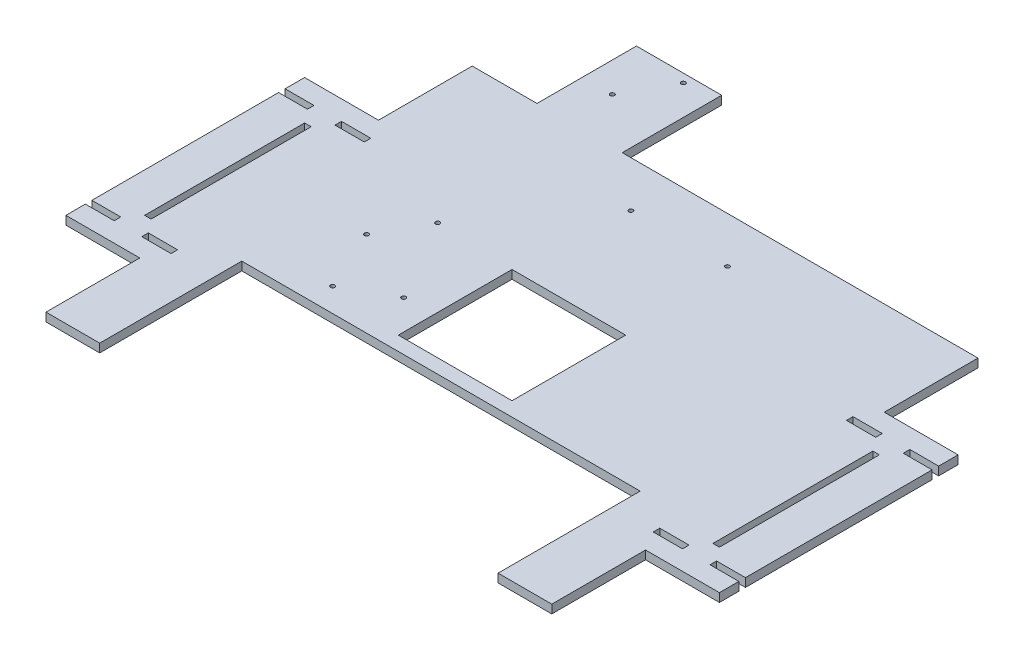
SolidWorks part; units mm, degrees
ref_plane "Front Plane" through (0, 0, 0) normal (0, 0, 1) x (1, 0, 0)
ref_plane "Top Plane" through (0, 0, 0) normal (0, 1, 0) x (1, 0, 0)
ref_plane "Right Plane" through (0, 0, 0) normal (1, 0, 0) x (0, 0, -1)
sketch "Sketch1" plane through (0, 0, 0) normal (0, 1, 0) x (1, 0, 0)
  line L1 (-57.5, -75) -> (57.5, -75)
  line L2 (-57.5, -75) -> (-57.5, 75)
  line L3 (-57.5, 75) -> (57.5, 75)
  line L4 (57.5, -75) -> (57.5, 75)
  line L5 (-57.5, -75) -> (57.5, 75) construction
  line L6 (-57.5, 75) -> (57.5, -75) construction
  point P0 (0, 0)
  dimension "D1" = 115
  dimension "D2" = 150
extrude "Boss-Extrude1" add sketch "Sketch1" against normal blind 3
sketch "Sketch2" plane through (0, 0, 0) normal (0, 1, 0) x (1, 0, 0)
  line L0 (0, 0) -> (-57.5, 75) construction
  line L1 (-57.5, 75) -> (-57.5, -75) construction
  line L2 (57.5, 75) -> (-57.5, 75) construction
  line L3 (0, 0) -> (57.5, 75) construction
  line L4 (57.5, -75) -> (57.5, 75) construction
  line L5 (0, 0) -> (-57.5, -75) construction
  line L6 (0, 0) -> (57.5, -75) construction
  line L15 (31.5, -42) -> (57.5, -42)
  line L16 (57.5, -42) -> (57.5, -108)
  line L17 (57.5, -108) -> (31.5, -108)
  line L18 (31.5, -108) -> (31.5, -42)
  line L19 (31.5, 108) -> (57.5, 108)
  line L20 (57.5, 108) -> (57.5, 42)
  line L21 (57.5, 42) -> (31.5, 42)
  line L22 (31.5, 42) -> (31.5, 108)
  line L23 (-57.5, -75) -> (57.5, -75) construction
  line L24 (12.6, -86.8) -> (12.6, -53.3) construction
  line L25 (-57.5, -75) -> (12.6, -75)
  line L26 (-57.5, -75) -> (-57.5, -25)
  line L27 (-57.5, -25) -> (12.6, -25)
  line L28 (12.6, -75) -> (12.6, -25)
  dimension "D7" = 66
  dimension "D8" = 26
  dimension "D9" = 66
  dimension "D10" = 26
  dimension "D11" = 33
  dimension "D12" = 33
  dimension "D2" = 50
extrude "Cut-Extrude1" cut sketch "Sketch2" against normal blind 3
sketch "Sketch5" plane through (0, -3, 0) normal (0, -1, 0) x (1, 0, 0)
  line L0 (57.5, -33) -> (57.5, -35) construction
  line L1 (57.5, -35) -> (47.5, -35) construction
  line L2 (47.5, -33) -> (57.5, -33) construction
  line L3 (47.5, -35) -> (47.5, -33) construction
  line L4 (37.5, -33) -> (37.5, -35) construction
  line L5 (37.5, -35) -> (27.5, -35) construction
  line L6 (27.5, -35) -> (27.5, -33) construction
  line L7 (27.5, -33) -> (37.5, -33) construction
  line L8 (43.5, -28) -> (41.5, -28) construction
  line L9 (41.5, -28) -> (41.5, 28) construction
  line L10 (43.5, 28) -> (43.5, -28) construction
  line L11 (41.5, 28) -> (43.5, 28) construction
  line L12 (57.5, 35) -> (57.5, 33) construction
  line L13 (57.5, 33) -> (47.5, 33) construction
  line L14 (47.5, 35) -> (57.5, 35) construction
  line L15 (47.5, 33) -> (47.5, 35) construction
  line L16 (27.5, 33) -> (27.5, 35) construction
  line L17 (37.5, 33) -> (27.5, 33) construction
  line L18 (37.5, 35) -> (37.5, 33) construction
  line L19 (27.5, 35) -> (37.5, 35) construction
  line L20 (57.5, -33) -> (57.5, -35) construction
  line L21 (57.5, -35) -> (47.5, -35) construction
  line L22 (47.5, -33) -> (57.5, -33) construction
  line L23 (47.5, -35) -> (47.5, -33) construction
  line L24 (37.5, -33) -> (37.5, -35) construction
  line L25 (37.5, -35) -> (27.5, -35) construction
  line L26 (27.5, -35) -> (27.5, -33) construction
  line L27 (27.5, -33) -> (37.5, -33) construction
  line L28 (43.5, -28) -> (41.5, -28) construction
  line L29 (41.5, -28) -> (41.5, 28) construction
  line L30 (43.5, 28) -> (43.5, -28) construction
  line L31 (41.5, 28) -> (43.5, 28) construction
  line L32 (57.5, 35) -> (57.5, 33) construction
  line L33 (57.5, 33) -> (47.5, 33) construction
  line L34 (47.5, 35) -> (57.5, 35) construction
  line L35 (47.5, 33) -> (47.5, 35) construction
  line L36 (27.5, 33) -> (27.5, 35) construction
  line L37 (37.5, 33) -> (27.5, 33) construction
  line L38 (37.5, 35) -> (37.5, 33) construction
  line L39 (27.5, 35) -> (37.5, 35) construction
  line L40 (27.35, 35.15) -> (37.65, 35.15)
  line L41 (37.65, 35.15) -> (37.65, 32.85)
  line L42 (37.65, 32.85) -> (27.35, 32.85)
  line L43 (27.35, 32.85) -> (27.35, 35.15)
  line L52 (43.65, -28.15) -> (41.35, -28.15)
  line L53 (41.35, -28.15) -> (41.35, 28.15)
  line L54 (41.35, 28.15) -> (43.65, 28.15)
  line L55 (43.65, 28.15) -> (43.65, -28.15)
  line L56 (57.65, 35.15) -> (57.65, 32.85)
  line L57 (57.65, 32.85) -> (47.35, 32.85)
  line L58 (47.35, 32.85) -> (47.35, 35.15)
  line L59 (47.35, 35.15) -> (57.65, 35.15)
  line L64 (37.65, -32.85) -> (37.65, -35.15)
  line L65 (37.65, -35.15) -> (27.35, -35.15)
  line L66 (27.35, -35.15) -> (27.35, -32.85)
  line L67 (27.35, -32.85) -> (37.65, -32.85)
  line L68 (57.65, -32.85) -> (57.65, -35.15)
  line L69 (57.65, -35.15) -> (47.35, -35.15)
  line L70 (47.35, -35.15) -> (47.35, -32.85)
  line L71 (47.35, -32.85) -> (57.65, -32.85)
  dimension "D1" = 0.15
  dimension "D2" = 0.15
  dimension "D3" = 0.15
  dimension "D4" = 0.15
  dimension "D5" = 0.15
extrude "Cut-Extrude2" cut sketch "Sketch5" against normal blind 3
mirror "Mirror1" about plane through (-57.5, -3, 75) normal (-1, 0, 0) of bodies 103
ref_plane "PlaneWhichWheelsRoll" through (0, -23, 0) normal (0, -1, 0) x (-1, 0, 0)
sketch "Sketch9" plane through (0, 0, -75) normal (0, 0, -1) x (-1, 0, 0)
  line L0 (-31.5, 0) -> (146.5, 0) construction
  line L2 (93.7, 0) -> (93.7, -3)
  line L3 (93.7, -3) -> (123.7, -3)
  line L4 (123.7, 0) -> (123.7, -3)
  line L5 (-31.5, -3) -> (146.5, -3) construction
  line L7 (93.7, 0) -> (123.7, 0)
  line L8 (101.2, 0) -> (116.2, 0) construction
  line L9 (101.2, 0) -> (116.2, 0) construction
  point P10 (108.7, 0)
  point P11 (108.7, 0)
  dimension "D1" = 30
extrude "Boss-Extrude2" add sketch "Sketch9" along normal blind 35
sketch "Sketch8" plane through (0, -3, 0) normal (0, -1, 0) x (1, 0, 0)
  line L1 (-77.5, -20) -> (-37.5, -20)
  line L2 (-77.5, -20) -> (-77.5, 20)
  line L3 (-77.5, 20) -> (-37.5, 20)
  line L4 (-37.5, -20) -> (-37.5, 20)
  line L5 (-77.5, -20) -> (-37.5, 20) construction
  line L6 (-77.5, 20) -> (-37.5, -20) construction
  circle A0 centre (-74.5, -58.8329) radius 0.75 construction
  circle A1 centre (-74.5, -58.8329) radius 0.75
  circle A2 centre (-40.5, -58.8329) radius 0.75 construction
  circle A3 centre (-40.5, -58.8329) radius 0.75
  circle A4 centre (-104.8, -21.1355) radius 0.75 construction
  circle A5 centre (-104.8, -21.1355) radius 0.75
  circle A6 centre (-113.8, -5.1355) radius 0.75 construction
  circle A7 centre (-113.8, -5.1355) radius 0.75
  circle A8 centre (-87.9808, 7.6414) radius 0.75 construction
  circle A9 centre (-87.9808, 7.6414) radius 0.75
  circle A10 centre (-103.9808, 16.6414) radius 0.75 construction
  circle A11 centre (-103.9808, 16.6414) radius 0.75
  circle A12 centre (-104.2, -107) radius 0.75 construction
  circle A13 centre (-104.2, -107) radius 0.75
  circle A14 centre (-113.2, -91) radius 0.75 construction
  circle A15 centre (-113.2, -91) radius 0.75
  circle A16 centre (-57.5, 0) radius 7 construction
  circle A17 centre (-57.5, 0) radius 7 construction
  dimension "D1" = 40
  dimension "D2" = 40
extrude "Cut-Extrude3" cut sketch "Sketch8" against normal through all
equation "\"x_WidthofBase\"=230"
equation "\"D1@Sketch1\"=\"x_WidthofBase\"/2"
equation "\"y_LengthofBaseofCar\"=150"
equation "\"D2@Sketch1\"=\"y_LengthofBaseofCar\""
equation "\"TB\"= 3'ThicknessofBase"
equation "\"D1@Boss-Extrude1\"=\"TB\""
equation "\"w_Wheelwidth\"=26"
equation "\"d_Wheeldiameter\"=66"
equation "\"D7@Sketch2\"=\"d_Wheeldiameter\""
equation "\"D8@Sketch2\"=\"w_Wheelwidth\""
equation "\"D9@Sketch2\"=\"d_Wheeldiameter\""
equation "\"D10@Sketch2\"=\"w_Wheelwidth\""
equation "\"D11@Sketch2\"=\"d_Wheeldiameter\"/2"
equation "\"D12@Sketch2\"=\"d_Wheeldiameter\"/2"
equation "\"D1@Cut-Extrude1\"=\"TB\""
